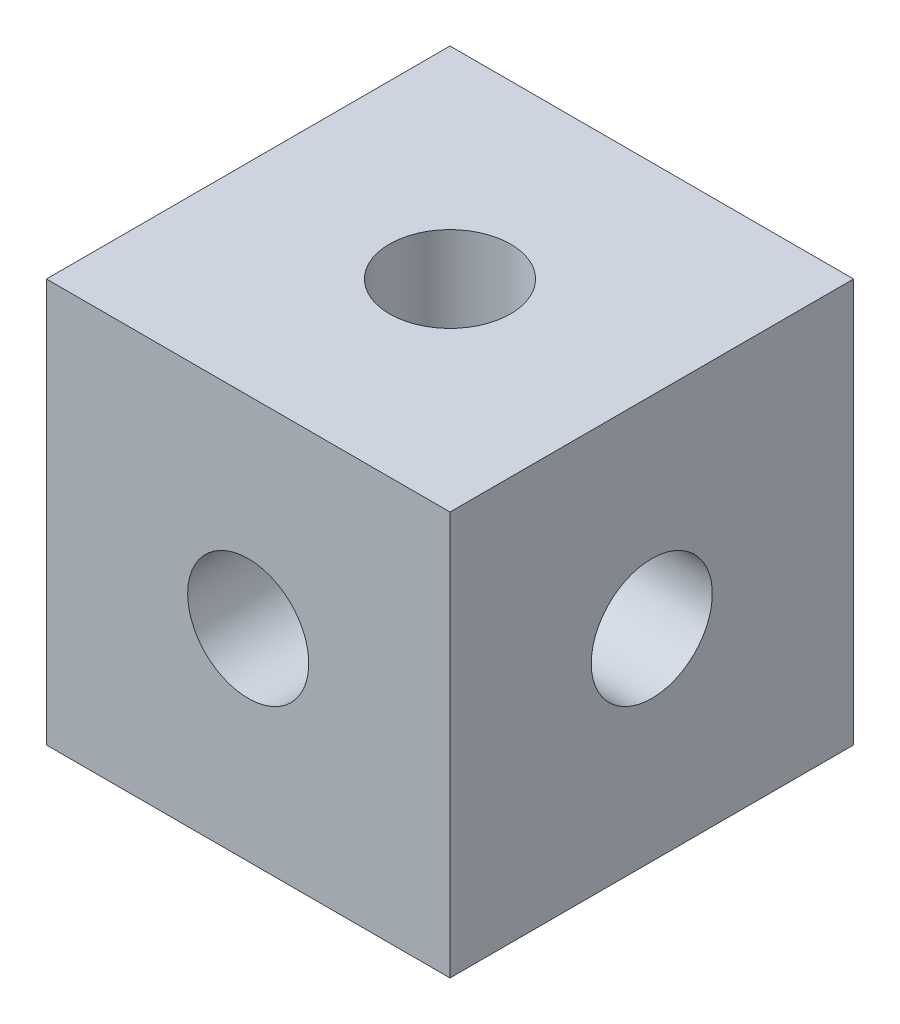
SolidWorks part; units mm, degrees
ref_plane "前视基准面" through (0, 0, 0) normal (0, 0, 1) x (1, 0, 0)
ref_plane "上视基准面" through (0, 0, 0) normal (0, 1, 0) x (1, 0, 0)
ref_plane "右视基准面" through (0, 0, 0) normal (1, 0, 0) x (0, 0, -1)
sketch "草图1" plane through (0, 0, 0) normal (0, 1, 0) x (1, 0, 0)
  line L0 (0, 5) -> (10, 5) construction
  line L1 (0, 0) -> (10, 0)
  line L2 (0, 0) -> (0, 10)
  line L3 (0, 10) -> (10, 10)
  line L4 (10, 0) -> (10, 10)
  circle A0 centre (5, 5) radius 1.5
  dimension "D2" = 3
  dimension "D1" = 10
extrude "凸台-拉伸1" add sketch "草图1" along normal blind 10
sketch "草图2" plane through (0, 0, 0) normal (0, 0, 1) x (1, 0, 0)
  line L0 (5, 10) -> (5, 0) construction
  line L1 (0, 10) -> (10, 10) construction
  line L2 (0, 0) -> (10, 0) construction
  circle A0 centre (5, 5) radius 1.5
  dimension "D1" = 3
extrude "切除-拉伸1" cut sketch "草图2" against normal through all both and the other way through all
sketch "草图3" plane through (0, 0, 0) normal (-1, 0, 0) x (0, 0, 1)
  line L0 (-5, 10) -> (-5, 0) construction
  line L1 (-10, 10) -> (0, 10) construction
  line L2 (-10, 0) -> (0, 0) construction
  circle A0 centre (-5, 5) radius 1.5
  dimension "D1" = 3
extrude "切除-拉伸2" cut sketch "草图3" against normal through all both and the other way through all
